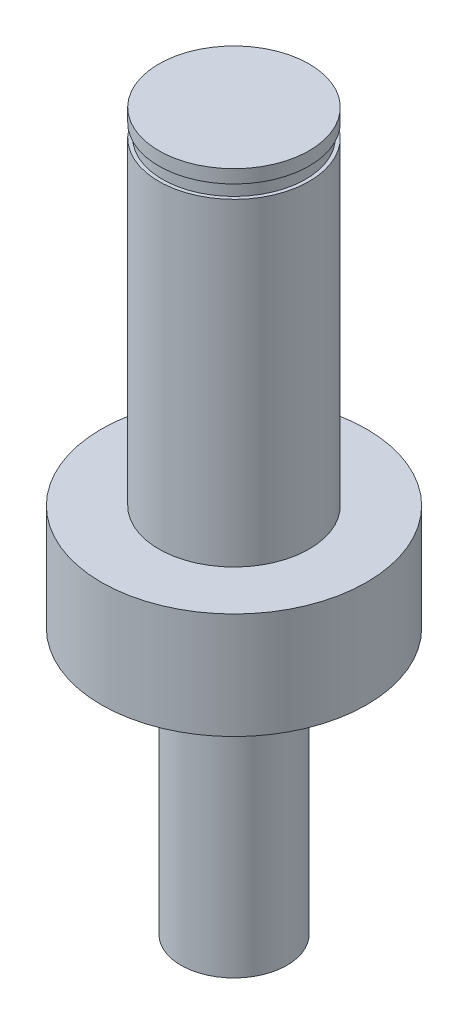
SolidWorks part; units mm, degrees
ref_plane "Front Plane" through (0, 0, 0) normal (0, 0, 1) x (1, 0, 0)
ref_plane "Top Plane" through (0, 0, 0) normal (0, 1, 0) x (1, 0, 0)
ref_plane "Right Plane" through (0, 0, 0) normal (1, 0, 0) x (0, 0, -1)
sketch "Sketch1" plane through (0, 0, 0) normal (0, 0, 1) x (1, 0, 0)
  line L0 (0, 0) -> (6, 0)
  line L1 (6, 0) -> (6, 30)
  line L2 (6, 30) -> (15, 30)
  line L3 (15, 30) -> (15, 42)
  line L4 (15, 42) -> (8.5, 42)
  line L5 (8.5, 42) -> (8.5, 81)
  line L6 (8.5, 81) -> (0, 81)
  line L7 (0, 81) -> (0, 0)
  line L8 (0, 0) -> (0, 97.4787) construction
  line L9 (8.5, 79.5) -> (8.1, 79.5)
  line L10 (8.1, 79.5) -> (8.1, 78)
  line L11 (8.1, 78) -> (8.5, 78)
  dimension "D1" = 12
  dimension "D2" = 30
  dimension "D3" = 30
  dimension "D4" = 12
  dimension "D5" = 17
  dimension "D6" = 36
  dimension "D7" = 1.5
  dimension "D8" = 1.5
  dimension "D9" = 16.2
revolve "Revolve1" add sketch "Sketch1" angle 360 about L8
